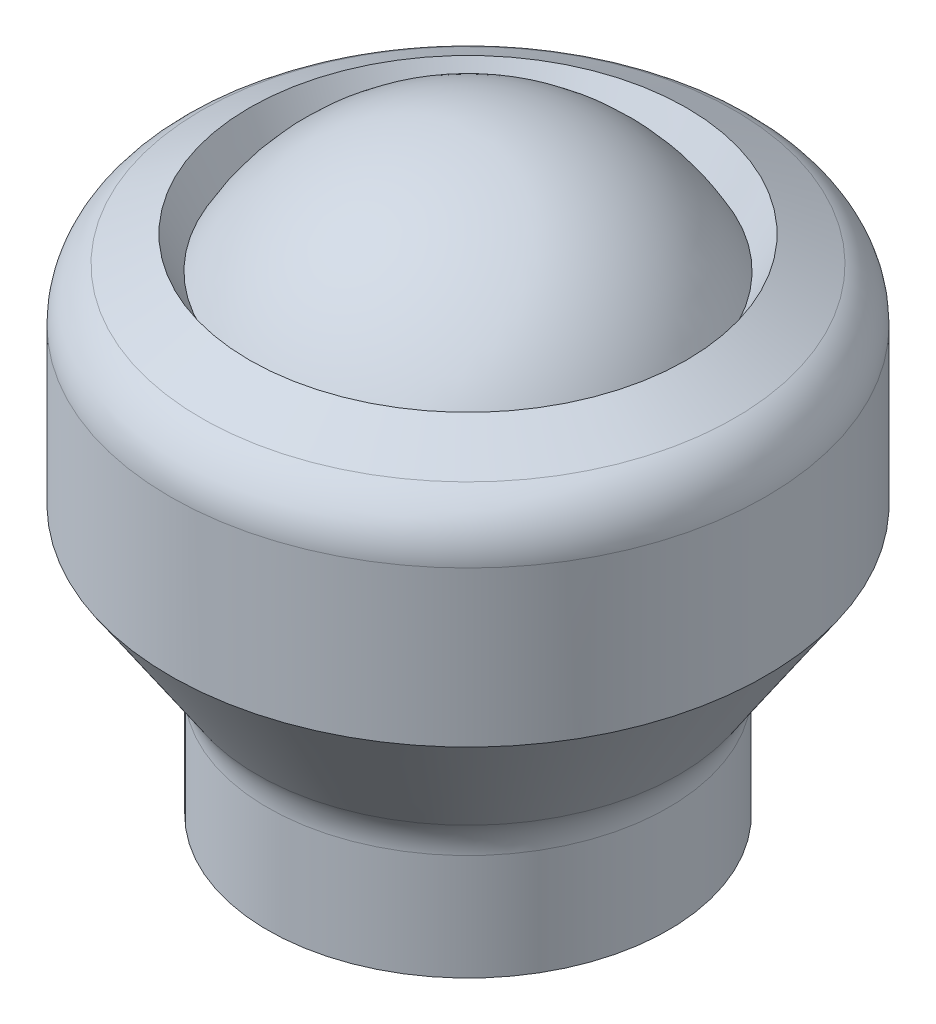
SolidWorks part; units mm, degrees
ref_plane "正面" through (0, 0, 0) normal (0, 0, 1) x (1, 0, 0)
ref_plane "平面" through (0, 0, 0) normal (0, 1, 0) x (1, 0, 0)
ref_plane "右側面" through (0, 0, 0) normal (1, 0, 0) x (0, 0, -1)
sketch "ｽｹｯﾁ1" plane through (0, 0, 0) normal (0, 0, 1) x (1, 0, 0)
  line L0 (34.4364, 27.1598) -> (34.4364, 7.4422)
  line L1 (34.4364, 7.4422) -> (34.4364, 4.4422)
  line L2 (34.4364, 4.4422) -> (36.4364, 4.4422)
  line L3 (36.4364, 4.4422) -> (36.4364, 7.4422)
  line L4 (36.4364, 7.4422) -> (41.1275, 7.4422)
  line L5 (41.1275, 7.4422) -> (41.1275, 11.5962)
  line L6 (41.1275, 11.5962) -> (44.3804, 16.4215)
  line L7 (44.3804, 16.4215) -> (44.3804, 22.7873)
  line L8 (44.3804, 22.7873) -> (41.7354, 24.2337)
  line L9 (41.7354, 24.2337) -> (41.1455, 23.155)
  circle A0 centre (34.4364, 19.5376) radius 7.6222
  arc A1 (34.4364, 27.1598) -> (41.1455, 23.155) centre (34.4364, 19.5376) cw
  point P14 (44.3804, 22.7873)
revolve "回転1" add sketch "ｽｹｯﾁ1" angle 360 about L0
fillet "ﾌｨﾚｯﾄ1" radius 2 2 edges at (24.4924, 22.7873, 0) (27.7454, 11.5962, 0)
